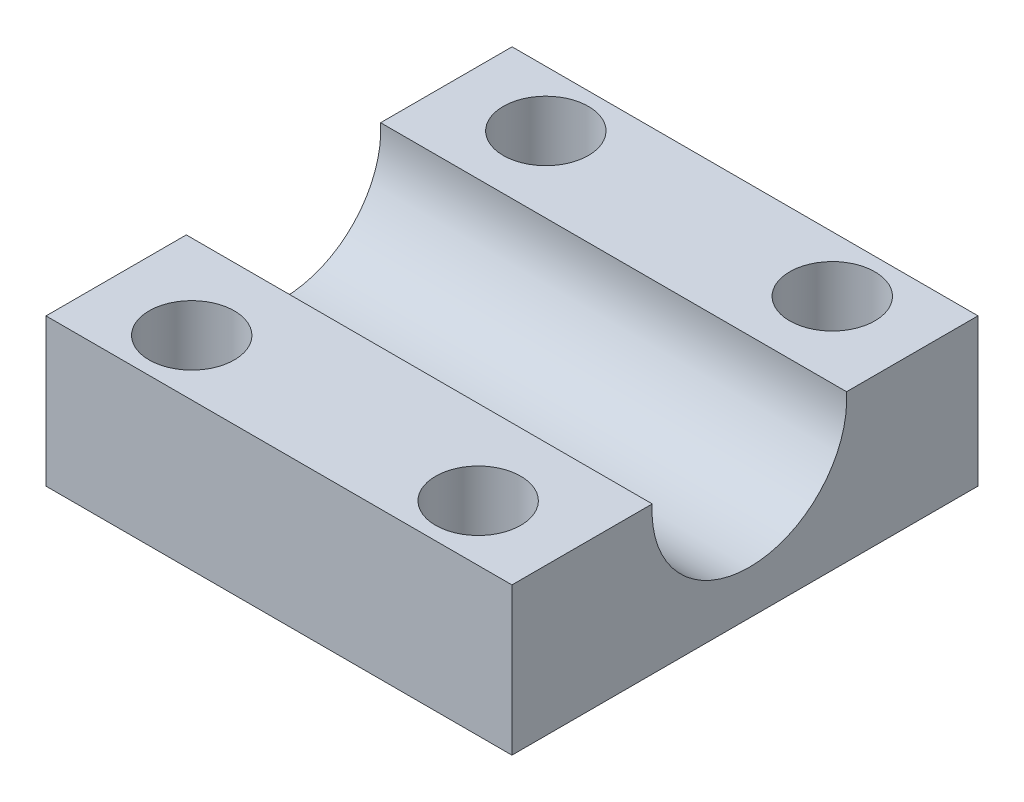
SolidWorks part; units mm, degrees
ref_plane "Front Plane" through (0, 0, 0) normal (0, 0, 1) x (1, 0, 0)
ref_plane "Top Plane" through (0, 0, 0) normal (0, 1, 0) x (1, 0, 0)
ref_plane "Right Plane" through (0, 0, 0) normal (1, 0, 0) x (0, 0, -1)
sketch "Sketch1" plane through (0, 0, 0) normal (0, 1, 0) x (1, 0, 0)
  line L6 (-19.145, 19.15) -> (19.145, 19.15)
  line L7 (-19.145, 19.15) -> (-19.145, -19.15)
  line L8 (-19.145, -19.15) -> (19.145, -19.15)
  line L9 (19.145, 19.15) -> (19.145, -19.15)
  line L10 (-19.145, 19.15) -> (19.145, -19.15) construction
  line L11 (-19.145, -19.15) -> (19.145, 19.15) construction
  point P11 (0, 0)
  dimension "D4" = 38.29
  dimension "D5" = 38.3
extrude "Boss-Extrude1" add sketch "Sketch1" along normal blind 12.12
sketch "Sketch2" plane through (19.145, 0, 0) normal (1, 0, 0) x (0, 0, -1)
  line L0 (-9.2164, 12.12) -> (-7.5, 7.11)
  line L1 (-19.15, 12.12) -> (19.15, 12.12) construction
  line L2 (-7.5, 7.11) -> (7.5, 7.11)
  line L3 (0, 7.11) -> (0, 0) construction
  line L4 (-9.2164, 12.12) -> (9.2164, 12.12)
  line L5 (9.2164, 12.12) -> (7.5, 7.11)
  line L6 (-19.15, 0) -> (19.15, 0) construction
  line L7 (-5.4456, 17.12) -> (6.1733, 17.12)
  line L8 (-7.6205, 12.12) -> (8.3482, 12.12)
  circle A0 centre (0.3638, 11.62) radius 8
  dimension "D2" = 16
  dimension "D1" = 7.11
  dimension "D3" = 15
  dimension "D5" = 2.5
  dimension "D6" = 5
extrude "Cut-Extrude1" cut sketch "Sketch2" against normal through all contours L4 A0 L2 | L3 L2 A0 | L2 L3 A0
hole_wizard "M8x1.0 Tapped Hole2" positions "Sketch6" profile "Sketch7" tap size "M8x1.0" standard "ANSI Metric" end condition through all
sketch "Sketch6" plane through (0, 12.12, 0) normal (0, 1, 0) x (1, 0, 0)
  line L0 (0, 0) -> (-19.145, 0) construction
  line L4 (0, 0) -> (0, 19.15) construction
  line L5 (19.145, 19.15) -> (-19.145, 19.15) construction
  line L8 (-19.145, 19.15) -> (-19.145, -19.15) construction
  circle A1 centre (-11.77, 14.55) radius 4.125
  circle A2 centre (11.77, 14.55) radius 4.125
  circle A3 centre (11.77, -14.55) radius 4.125
  circle A4 centre (-11.77, -14.55) radius 4.125
  point P0 (-11.77, 14.55)
  point P18 (11.77, 14.55)
  point P25 (-11.77, -14.55)
  point P26 (11.77, -14.55)
  dimension "D1" = 8.25
  dimension "D2" = 15.29
  dimension "D3" = 20.85
sketch "Sketch7" plane through (-11.77, 12.12, -14.55) normal (1, 0, 0) x (0, 0, 1)
  line L0 (0, 0) -> (0, 12.12)
  line L1 (0, 12.12) -> (3.5, 12.12)
  line L2 (3.5, 12.12) -> (3.5, 0)
  line L5 (3.5, 0) -> (0, 0)
  line L11 (0, -6.35) -> (0, 107.95) construction
  dimension "Thru Tap Drill Dia." = 7
  dimension "Thru Tap Drill Depth" = 12.12
cosmetic thread "Hole Thread5" parameters "D2"=8
cosmetic thread "Hole Thread9" parameters "D2"=8
cosmetic thread "Hole Thread10" parameters "D2"=8
cosmetic thread "Hole Thread11" parameters "D2"=8
mirror "Mirror1" about plane through (0, 0, 0) normal (0, 0, 1) of "M8x1.0 Tapped Hole2" second plane through (0, 0, 0) second plane normal (1, 0, 0)
cosmetic thread "Hole Thread6" parameters "D2"=8
cosmetic thread "Hole Thread7" parameters "D2"=8
cosmetic thread "Hole Thread8" parameters "D2"=8
